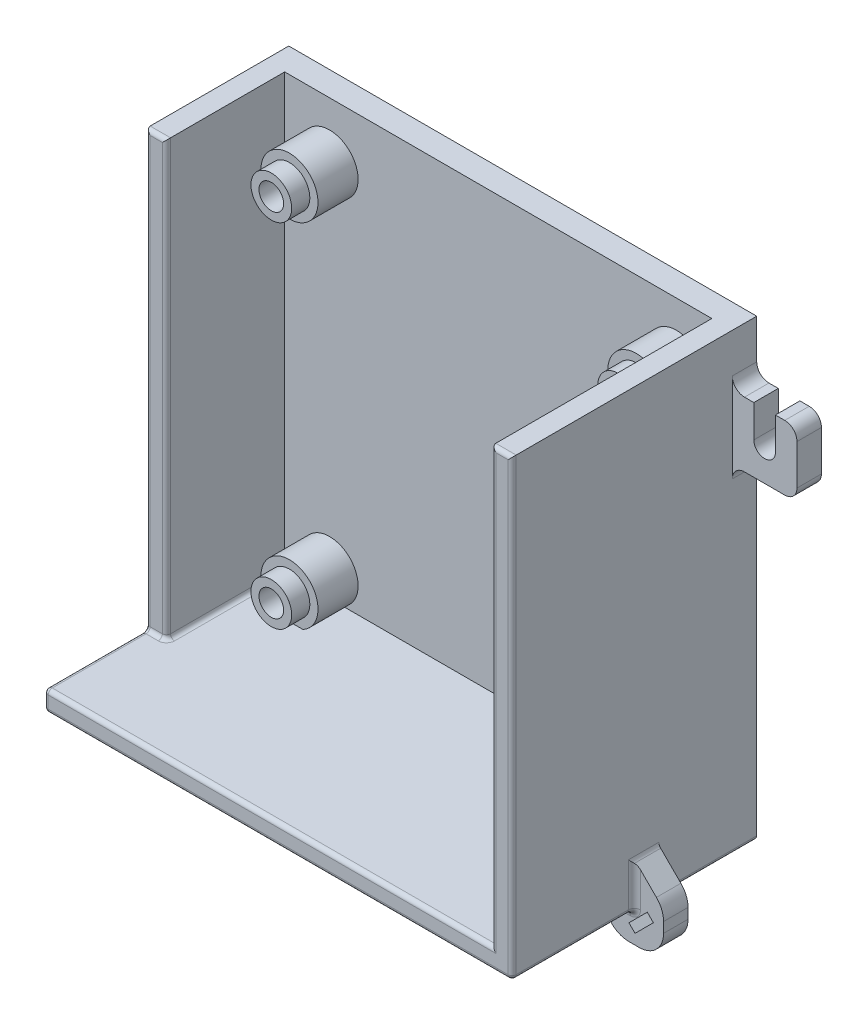
SolidWorks part; units mm, degrees
material "ABS"
ref_plane "X-Y Datum" through (0, 0, 0) normal (0, 0, 1) x (1, 0, 0)
ref_plane "X-Z Datum" through (0, 0, 0) normal (0, 1, 0) x (1, 0, 0)
ref_plane "Y-Z Datum" through (0, 0, 0) normal (1, 0, 0) x (0, 0, -1)
sketch "Sketch1" plane through (0, 0, 0) normal (0, 0, 1) x (1, 0, 0)
  line L1 (-52.3875, 53.1812) -> (52.3875, 53.1812)
  line L2 (-52.3875, 53.1812) -> (-52.3875, -53.1812)
  line L3 (-52.3875, -53.1812) -> (52.3875, -53.1812)
  line L4 (52.3875, 53.1812) -> (52.3875, -53.1812)
  line L5 (-52.3875, 53.1812) -> (52.3875, -53.1812) construction
  line L6 (-52.3875, -53.1812) -> (52.3875, 53.1812) construction
  point P0 (0, 0)
  dimension "D1" = 104.775
  dimension "D2" = 106.3625
extrude "Boss-Extrude1" add sketch "Sketch1" along normal blind 6
sketch "Sketch2" plane through (0, 0, 0) normal (0, 0, 1) x (1, 0, 0)
  line L1 (-57.3875, -53.1812) -> (-57.3875, -58.1813)
  line L2 (-57.3875, 53.1812) -> (-57.3875, -53.1812)
  line L4 (57.3875, 53.1812) -> (52.3875, 53.1812)
  line L5 (57.3875, -58.1812) -> (57.3875, 53.1812)
  line L6 (-52.3875, -58.1812) -> (57.3875, -58.1812)
  line L7 (57.3875, -58.1812) -> (57.3875, 53.1812)
  line L8 (-52.3875, -58.1812) -> (57.3875, -58.1812)
  line L9 (52.3875, -53.1812) -> (52.3875, 53.1812) construction
  line L10 (-52.3875, -53.1812) -> (52.3875, -53.1812) construction
  line L11 (52.3875, -53.1812) -> (52.3875, 53.1812)
  line L12 (-52.3875, -53.1812) -> (52.3875, -53.1812)
  line L13 (-57.3875, 53.1812) -> (-57.3875, -53.1812)
  line L14 (-57.3875, -58.1813) -> (-52.3875, -58.1812)
  line L15 (-57.3875, 53.1812) -> (-52.3875, 53.1812)
  line L16 (-52.3875, 53.1812) -> (-52.3875, -53.1812) construction
  line L17 (-52.3875, 53.1812) -> (-52.3875, -53.1812)
  dimension "D1" = 5
  dimension "D2" = 5
extrude "Boss-Extrude2" add sketch "Sketch2" along normal blind 35
sketch "Sketch3" plane through (0, 0, 6) normal (0, 0, 1) x (1, 0, 0)
  circle A0 centre (-41.382, 39.351) radius 3.025
  circle A1 centre (43.708, 39.351) radius 3.025
  circle A2 centre (43.708, -47.009) radius 3.025
  circle A3 centre (-41.382, -47.009) radius 3.025
  circle A4 centre (43.708, 39.351) radius 5
  circle A5 centre (-41.382, 39.351) radius 5
  circle A6 centre (-41.382, -47.009) radius 5
  circle A7 centre (43.708, -47.009) radius 5
  point P0 (-41.382, 39.351)
  point P1 (-41.382, -47.009)
  point P3 (43.708, -47.009)
  point P5 (43.708, 39.351)
  dimension "D1" = 6.05
  dimension "D2" = 10
extrude "Boss-Extrude3" add sketch "Sketch3" along normal blind 14.2875
sketch "Sketch4" plane through (0, 0, 6) normal (0, 0, 1) x (1, 0, 0)
  circle A0 centre (43.708, 39.351) radius 7
  circle A1 centre (-41.382, 39.351) radius 7
  circle A2 centre (-41.382, -47.009) radius 7
  circle A3 centre (43.708, -47.009) radius 7
  circle A5 centre (-41.382, -47.009) radius 3.025
  circle A6 centre (-41.382, -47.009) radius 3.025
  circle A7 centre (43.708, -47.009) radius 3.025
  circle A8 centre (43.708, -47.009) radius 3.025
  circle A9 centre (43.708, 39.351) radius 3.025
  circle A10 centre (43.708, 39.351) radius 3.025
  circle A11 centre (-41.382, 39.351) radius 3.025
  circle A12 centre (-41.382, 39.351) radius 3.025
  dimension "D1" = 14
  dimension "D2" = 0
  dimension "D3" = 0
  dimension "D4" = 0
  dimension "D5" = 0
extrude "Boss-Extrude4" add sketch "Sketch4" along normal blind 9.8425
sketch "Sketch6" plane through (0, 0, 0) normal (0, 0, 1) x (1, 0, 0)
  line L0 (-73.2675, -42.3012) -> (-57.3875, -58.1813) construction
  line L5 (57.3875, -58.1812) -> (57.3875, 53.1812) construction
  line L6 (57.3875, 40.4812) -> (73.2625, 40.4812)
  line L7 (57.3875, 40.4812) -> (57.3875, 24.6062)
  line L8 (57.3875, 24.6062) -> (73.2625, 24.6062)
  line L9 (73.2625, 40.4812) -> (73.2625, 24.6062)
  line L10 (57.3875, 24.6062) -> (73.2625, 40.4812)
  line L11 (57.3875, 53.1812) -> (52.3875, 53.1812) construction
  line L13 (-57.3875, -58.1813) -> (-73.2675, -58.1813)
  line L14 (-57.3875, -58.1813) -> (-57.3875, -42.3012)
  line L15 (-57.3875, -42.3012) -> (-73.2675, -42.3012)
  line L17 (-73.2675, -58.1813) -> (-73.2675, -42.3012)
  circle A1 centre (65.325, 32.5438) radius 2 construction
  circle A2 centre (-65.3275, -50.2413) radius 2 construction
  dimension "D1" = 15.88
  dimension "D6" = 4
  dimension "D2" = 4
  dimension "D4" = 15.875
  dimension "D5" = 15.875
  dimension "D7" = 12.7
extrude "Boss-Extrude5" add sketch "Sketch6" along normal blind 6
hole_wizard "M5 Clearance Hole2" positions "Sketch7" profile "Sketch8" hole size "M5" standard "ANSI Metric" end condition through all
sketch "Sketch7" plane through (0, 0, 6) normal (0, 0, 1) x (1, 0, 0)
  point P0 (65.325, 32.5438)
  point P8 (-65.3275, -50.2413)
sketch "Sketch8" plane through (65.325, 32.5438, 6) normal (1, 0, 0) x (0, -1, 0)
  line L0 (0, 0) -> (0, 6)
  line L1 (0, 6) -> (2.65, 6)
  line L2 (2.65, 6) -> (2.65, 0)
  line L5 (2.65, 0) -> (0, 0)
  line L11 (0, -6.35) -> (0, 107.95) construction
  dimension "Thru Hole Dia." = 5.3
  dimension "Thru Hole Depth" = 6
fillet "Fillet2" radius 3 6 edges at (73.2625, 24.6062, 3) (73.2625, 40.4812, 3) (57.3875, 40.4812, 3) (57.3875, 24.6062, 3) (-73.2675, -58.1813, 3) (-73.2675, -42.3012, 3)
sketch "Sketch9" plane through (0, 0, 35) normal (0, 0, 1) x (1, 0, 0)
  line L0 (-52.3875, 38.1812) -> (-57.3875, 38.1812)
  line L1 (-52.3875, -53.1812) -> (-57.3875, -53.1812)
  line L8 (-52.3875, -53.1812) -> (-52.3875, 53.1812)
  line L9 (-52.3875, 53.1812) -> (-57.3875, 53.1812)
  line L10 (-57.3875, 53.1812) -> (-57.3875, -58.1813)
  line L11 (-57.3875, -58.1813) -> (57.3875, -58.1812)
  line L12 (57.3875, -58.1812) -> (57.3875, 53.1812)
  line L13 (57.3875, 53.1812) -> (52.3875, 53.1812)
  line L14 (52.3875, 53.1812) -> (52.3875, -53.1812)
  line L15 (52.3875, -53.1812) -> (-52.3875, -53.1812)
  line L16 (-52.3875, -53.1812) -> (-52.3875, 53.1812)
  line L17 (-52.3875, 53.1812) -> (-57.3875, 53.1812)
  line L18 (-57.3875, 53.1812) -> (-57.3875, -58.1813)
  line L19 (-57.3875, -58.1813) -> (57.3875, -58.1812)
  line L20 (57.3875, -58.1812) -> (57.3875, 53.1812)
  line L21 (57.3875, 53.1812) -> (52.3875, 53.1812)
  line L22 (52.3875, 53.1812) -> (52.3875, -53.1812)
  line L23 (52.3875, -53.1812) -> (-52.3875, -53.1812)
  line M12 (-57.3875, 53.1812) -> (-57.3875, -58.1813)
  line M13 (-57.3875, -58.1813) -> (57.3875, -58.1812)
  line M14 (57.3875, -58.1812) -> (57.3875, 53.1812)
  line M15 (57.3875, 53.1812) -> (52.3875, 53.1812)
  line M16 (52.3875, 53.1812) -> (52.3875, -53.1812)
  line M17 (52.3875, -53.1812) -> (-52.3875, -53.1812)
  dimension "D2" = 15
  dimension "D1" = 0
extrude "Boss-Extrude6" add sketch "Sketch9" along normal blind 25 contours L1 M17 M12 M13 M14 M15 M16 | L16 L17 L18 L19 L20 L21 L22 L23
fillet "Fillet3" radius 1 14 edges at (-54.8875, 53.1812, 35) (-54.8875, -53.1812, 35) (57.3875, -58.1812, 30) (-57.3875, 0, 35) (-52.3875, 0, 35) (-52.3875, -53.1812, 20.5) (-57.3875, -58.1813, 33) (-57.3875, -53.1812, 47.5) (52.3875, 0, 60) (54.8875, 53.1812, 60) (57.3875, -2.5, 60) (0, -58.1813, 60) (-57.3875, -55.6812, 60) (-2.5, -53.1812, 60)
ref_plane "Plane1" through (0, 0, 30) normal (0, 0, -1) x (-1, 0, 0)
sketch "Sketch10" plane through (0, 0, 30) normal (0, 0, -1) x (-1, 0, 0)
  line L0 (-56.3875, -57.1812) -> (56.3875, -57.1812) construction
  line L1 (56.3875, -57.1812) -> (56.3875, -58.1812) construction
  line L2 (56.3875, -58.1812) -> (-56.3875, -58.1812) construction
  line L3 (-57.3875, -57.1812) -> (-57.3875, 53.1812) construction
  line L4 (-57.3875, 53.1812) -> (-56.3875, 52.1812) construction
  line L5 (-56.3875, 52.1812) -> (-56.3875, -57.1812) construction
  line L6 (-56.3875, -58.1812) -> (56.3875, -58.1812) construction
  line L7 (-56.3875, -57.1812) -> (56.3875, -57.1812)
  line L8 (56.3875, -57.1812) -> (56.3875, -58.1812)
  line L9 (56.3875, -58.1812) -> (-56.3875, -58.1812)
  line L10 (-57.3875, -57.1812) -> (-57.3875, 53.1812)
  line L11 (-57.3875, 53.1812) -> (-56.3875, 52.1812)
  line L12 (-56.3875, 52.1812) -> (-56.3875, -57.1812)
  line L13 (-56.3875, -58.1812) -> (56.3875, -58.1812)
  line L14 (-53.3875, -54.1812) -> (-59.0444, -59.8381)
  line L15 (-53.5444, -65.3381) -> (-46.3875, -58.1813)
  line L16 (-53.5444, -54.3381) -> (-64.5444, -54.3381)
  line L17 (-53.5444, -54.3381) -> (-53.5444, -65.3381)
  line L18 (-53.5444, -65.3381) -> (-64.5444, -65.3381)
  line L19 (-64.5444, -54.3381) -> (-64.5444, -65.3381)
  line L20 (-53.5444, -54.3381) -> (-64.5444, -65.3381) construction
  line L21 (-53.5444, -65.3381) -> (-64.5444, -54.3381) construction
  line L26 (-62.0444, -58.3381) -> (-60.5444, -56.8381)
  line L27 (-56.0444, -58.3381) -> (-62.0444, -58.3381)
  line L28 (-64.5444, -54.3381) -> (-57.3875, -47.1813)
  line L29 (-56.0444, -58.3381) -> (-56.0444, -61.3381)
  line L30 (-56.0444, -61.3381) -> (-62.0444, -61.3381)
  line L31 (-62.0444, -58.3381) -> (-62.0444, -61.3381)
  line L32 (-56.0444, -58.3381) -> (-62.0444, -61.3381) construction
  line L33 (-56.0444, -61.3381) -> (-62.0444, -58.3381) construction
  line L34 (-57.5444, -56.8381) -> (-60.5444, -56.8381)
  line L35 (-57.5444, -56.8381) -> (-57.5444, -62.8381)
  line L36 (-57.5444, -62.8381) -> (-60.5444, -62.8381)
  line L37 (-60.5444, -56.8381) -> (-60.5444, -62.8381)
  line L38 (-57.5444, -56.8381) -> (-60.5444, -62.8381) construction
  line L39 (-57.5444, -62.8381) -> (-60.5444, -56.8381) construction
  line L40 (-57.5444, -62.8381) -> (-56.0444, -61.3381)
  line L41 (-56.0444, -61.3381) -> (-60.5444, -56.8381)
  line L42 (-57.5444, -62.8381) -> (-62.0444, -58.3381)
  arc A0 (-57.3875, -57.1812) -> (-56.3875, -58.1812) centre (-56.3875, -57.1812) ccw construction
  arc A1 (-57.3875, -57.1812) -> (-56.3875, -58.1812) centre (-56.3875, -57.1812) ccw
  dimension "D1" = 3
  dimension "D2" = 11
  dimension "D3" = 11
  dimension "D4" = 45
  dimension "D5" = 45
  dimension "D6" = 6
  dimension "D7" = 8
  dimension "D8" = 3
  dimension "D9" = 6
  dimension "D10" = 6.364
extrude "Boss-Extrude7" add sketch "Sketch10" along normal blind 6
fillet "Fillet4" radius 6 3 edges at (64.5444, -54.3381, 27) (64.5444, -65.3381, 27) (53.5444, -65.3381, 27)
fillet "Fillet5" radius 1.5 5 edges at (57.3875, -52.1813, 30) (57.0946, -57.8884, 30) (57.3875, -47.1813, 27) (46.3875, -58.1813, 27) (51.3875, -58.1813, 30)
sketch "Sketch11" plane through (0, 0, 6) normal (0, 0, 1) x (1, 0, 0)
  line L0 (-67.9775, -50.2413) -> (-67.9775, -42.3012)
  line L1 (-57.3875, -42.3012) -> (-70.2675, -42.3012) construction
  line L2 (-62.6775, -50.2413) -> (-62.6775, -42.3012)
  line L3 (62.675, 32.5438) -> (62.675, 40.4812)
  line L4 (60.3875, 40.4812) -> (70.2625, 40.4812) construction
  line L5 (67.975, 32.5438) -> (67.975, 40.4812)
  line L6 (60.3875, 40.4812) -> (70.2625, 40.4812)
  line L7 (-57.3875, -42.3012) -> (-70.2675, -42.3012)
  circle A0 centre (-65.3275, -50.2413) radius 2.65 construction
  circle A1 centre (65.325, 32.5438) radius 2.65 construction
  circle A2 centre (65.325, 32.5438) radius 2.65
  circle A3 centre (-65.3275, -50.2413) radius 2.65
  point P16 (67.975, 32.5438)
  circle M1 centre (-65.3275, -50.2413) radius 2.65
  line M7 (-57.3875, -42.3012) -> (-70.2675, -42.3012)
extrude "Cut-Extrude1" cut sketch "Sketch11" against normal through all contours L2 L0 M1 M7 | A2 L5 L6 L3
